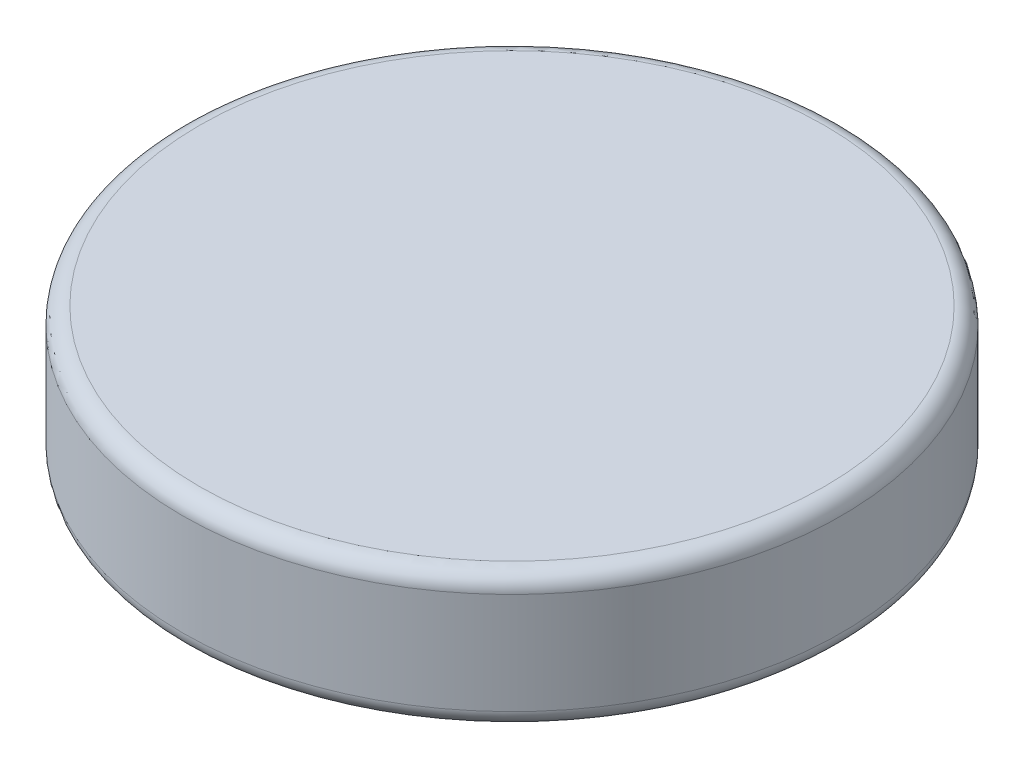
SolidWorks part; units mm, degrees
material "A286 Iron Base Superalloy"
ref_plane "Front Plane" through (0, 0, 0) normal (0, 0, 1) x (1, 0, 0)
ref_plane "Top Plane" through (0, 0, 0) normal (0, 1, 0) x (1, 0, 0)
ref_plane "Right Plane" through (0, 0, 0) normal (1, 0, 0) x (0, 0, -1)
sketch "Sketch1" plane through (0, 0, 0) normal (0, 1, 0) x (1, 0, 0)
  circle A0 centre (0, 0) radius 4.953
  dimension "D1" = 9.906
extrude "Boss-Extrude1" add sketch "Sketch1" along normal blind 2.032 contours A0
fillet "Fillet1" radius 0.254 2 edges at (0, 0, 4.953) (0, 2.032, 4.953)
